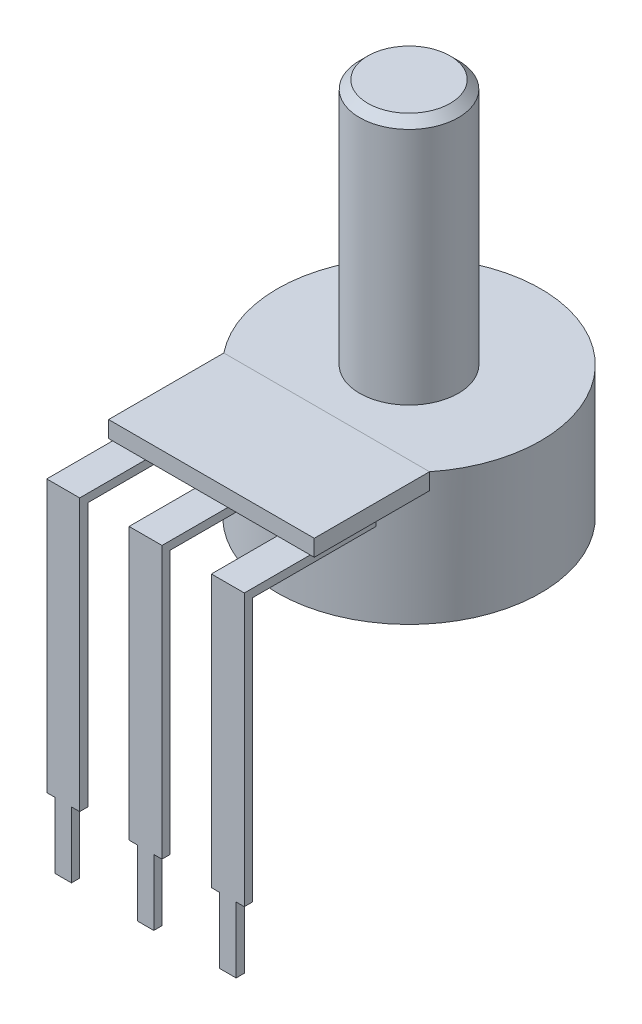
SolidWorks part; units mm, degrees
ref_plane "Front Plane" through (0, 0, 0) normal (0, 0, 1) x (1, 0, 0)
ref_plane "Top Plane" through (0, 0, 0) normal (0, 1, 0) x (1, 0, 0)
ref_plane "Right Plane" through (0, 0, 0) normal (1, 0, 0) x (0, 0, -1)
sketch "Sketch1" plane through (0, 0, 0) normal (0, 1, 0) x (1, 0, 0)
  circle A0 centre (0, 0) radius 8
extrude "Boss-Extrude1" add sketch "Sketch1" against normal blind 8
sketch "Sketch3" plane through (0, 0, 0) normal (0, 1, 0) x (1, 0, 0)
  circle A0 centre (0, 0) radius 3
  dimension "D1" = 6
extrude "Boss-Extrude2" add sketch "Sketch3" along normal blind 15
chamfer "Chamfer1" distance 0.5 angle 45 1 edges at (0, 15, 3)
sketch "Sketch2" plane through (0, 0, 0) normal (0, 1, 0) x (1, 0, 0)
  line L0 (0, 0) -> (0, -8) construction
  line L1 (-6.245, -5) -> (6.245, -5) construction
  line L3 (-9.9295, -11) -> (9.9295, -11)
  line L4 (-9.9295, -11) -> (-9.9295, -5)
  line L5 (-9.9295, -5) -> (9.9295, -5)
  line L6 (9.9295, -11) -> (9.9295, -5)
  line L7 (-9.9295, -11) -> (9.9295, -5) construction
  line L8 (-9.9295, -5) -> (9.9295, -11) construction
  circle A0 centre (0, 0) radius 8 construction
  point P9 (0, -5)
  point P10 (0, -5)
  dimension "D1" = 3
extrude "Cut-Extrude2" cut sketch "Sketch2" against normal blind 1
sketch "Sketch4" plane through (0, -1, 0) normal (0, 1, 0) x (1, 0, 0)
  line L0 (-6.245, -5) -> (6.245, -5)
  line L1 (-6.245, -5) -> (-6.245, -12)
  line L2 (6.245, -5) -> (6.245, -12)
  line L3 (-6.245, -12) -> (6.245, -12)
  dimension "D1" = 7
extrude "Boss-Extrude3" add sketch "Sketch4" along normal blind 1 separate body
sketch "Sketch5" plane through (0, -1, 0) normal (0, -1, 0) x (1, 0, 0)
  line L0 (-1, 16) -> (-1, 8)
  line L1 (-6, 16) -> (-4, 16)
  line L2 (-6, 16) -> (-6, 8)
  line L3 (-6, 8) -> (-4, 8)
  line L4 (-4, 16) -> (-4, 8)
  line L5 (-6, 16) -> (-4, 8) construction
  line L6 (-6, 8) -> (-4, 16) construction
  line L7 (-1, 16) -> (1, 16)
  line L8 (1, 16) -> (1, 8)
  line L9 (-1, 8) -> (1, 8)
  line L10 (4, 16) -> (4, 8)
  line L11 (4, 16) -> (6, 16)
  line L12 (6, 16) -> (6, 8)
  line L13 (4, 8) -> (6, 8)
  point P0 (-5, 12)
  dimension "D1" = 2
  dimension "D2" = 8
  dimension "D3" = 16
  dimension "D4" = 5
  dimension "D5" = 3
extrude "Boss-Extrude5" add sketch "Sketch5" along normal blind 0.5 separate body
sketch "Sketch6" plane through (0, -1.5, 0) normal (0, -1, 0) x (-1, 0, 0)
  line L0 (6, -16) -> (4, -16)
  line L1 (6, -16) -> (6, -15.5)
  line L2 (4, -16) -> (4, -15.5)
  line L3 (6, -15.5) -> (4, -15.5)
  line L4 (1, -16) -> (-1, -16)
  line L5 (1, -16) -> (1, -15.5)
  line L6 (1, -15.5) -> (-1, -15.5)
  line L7 (-1, -16) -> (-1, -15.5)
  line L8 (-4, -16) -> (-6, -16)
  line L9 (-4, -16) -> (-4, -15.5)
  line L10 (-4, -15.5) -> (-6, -15.5)
  line L11 (-6, -16) -> (-6, -15.5)
  dimension "D1" = 0.5
  dimension "D2" = 3
extrude "Boss-Extrude6" add sketch "Sketch6" along normal blind 16
sketch "Sketch7" plane through (0, -17.5, 0) normal (0, -1, 0) x (-1, 0, 0)
  line L0 (6, -15.75) -> (4, -15.75) construction
  line L1 (6, -16) -> (6, -15.5) construction
  line L2 (4, -15.5) -> (4, -16) construction
  line L3 (0.5, -15.5) -> (0.5, -16)
  line L4 (4, -16) -> (6, -16) construction
  line L6 (5.5, -15.5) -> (4.5, -15.5)
  line L7 (5.5, -15.5) -> (5.5, -16)
  line L8 (5.5, -16) -> (4.5, -16)
  line L9 (4.5, -15.5) -> (4.5, -16)
  line L10 (5.5, -15.5) -> (4.5, -16) construction
  line L11 (5.5, -16) -> (4.5, -15.5) construction
  line L12 (0.5, -15.5) -> (-0.5, -15.5)
  line L13 (-0.5, -15.5) -> (-0.5, -16)
  line L14 (0.5, -16) -> (-0.5, -16)
  line L15 (-4.5, -15.5) -> (-4.5, -16)
  line L16 (-4.5, -15.5) -> (-5.5, -15.5)
  line L17 (-5.5, -15.5) -> (-5.5, -16)
  line L18 (-4.5, -16) -> (-5.5, -16)
  point P6 (5, -15.75)
  dimension "D1" = 1
  dimension "D2" = 3
extrude "Boss-Extrude7" add sketch "Sketch7" along normal blind 4
